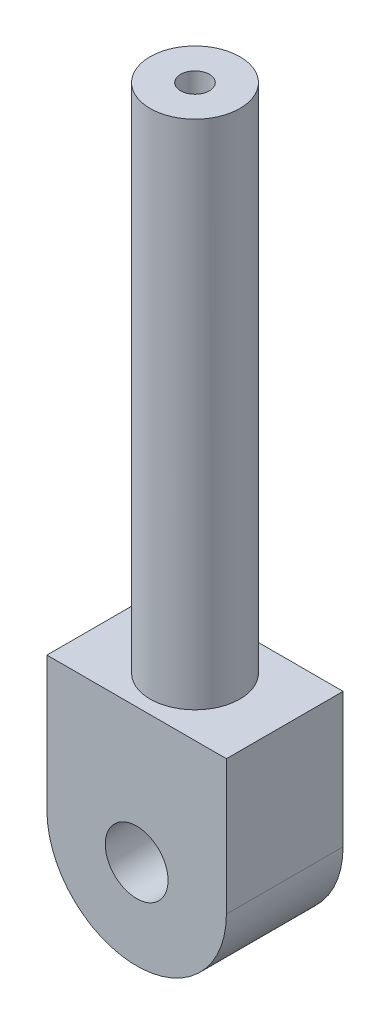
SolidWorks part; units mm, degrees
ref_plane "Plano frontal" through (0, 0, 0) normal (0, 0, 1) x (1, 0, 0)
ref_plane "Plano superior" through (0, 0, 0) normal (0, 1, 0) x (1, 0, 0)
ref_plane "Plano direito" through (0, 0, 0) normal (1, 0, 0) x (0, 0, -1)
sketch "Esboço1" plane through (0, 0, 0) normal (0, 0, 1) x (1, 0, 0)
  line L0 (0, 0) -> (0, 15) construction
  line L1 (-10, 15) -> (10, 15) construction
  line L2 (-10, 0) -> (-10, 15)
  line L3 (10, 0) -> (10, 15)
  line L4 (10, 15) -> (-10, 15)
  arc A0 (-10, 0) -> (10, 0) centre (0, 0) ccw
  circle A1 centre (0, 0) radius 3.5
  dimension "D1" = 10
  dimension "D2" = 7
  dimension "D3" = 15
extrude "Ressalto-extrusão1" add sketch "Esboço1" along normal blind 13
sketch "Esboço2" plane through (0, 15, 0) normal (0, 1, 0) x (1, 0, 0)
  line L0 (-10, -6.5) -> (10, -6.5) construction
  line L1 (-10, -13) -> (-10, 0) construction
  line L2 (10, -13) -> (10, 0) construction
  line L3 (0, 0) -> (0, -6.5) construction
  circle A0 centre (0, -6.5) radius 5
  dimension "D1" = 10
extrude "Ressalto-extrusão2" add sketch "Esboço2" along normal blind 57
sketch "Esboço3" plane through (0, 72, 0) normal (0, 1, 0) x (1, 0, 0)
  circle A0 centre (0, -6.5) radius 1.6
  dimension "D1" = 3.2
extrude "Corte-extrusão1" cut sketch "Esboço3" against normal blind 34
